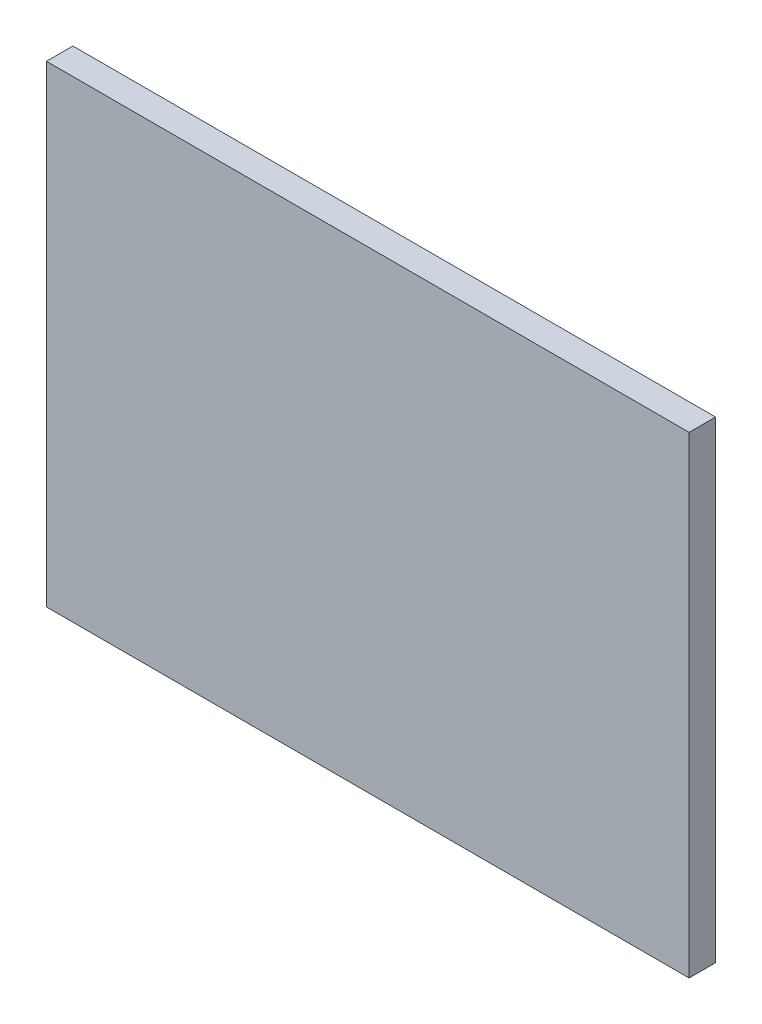
SolidWorks part; units mm, degrees
ref_plane "前视" through (0, 0, 0) normal (0, 0, 1) x (1, 0, 0)
ref_plane "上视" through (0, 0, 0) normal (0, 1, 0) x (1, 0, 0)
ref_plane "右视" through (0, 0, 0) normal (1, 0, 0) x (0, 0, -1)
sketch "草图1" plane through (0, 0, 0) normal (0, 0, 1) x (1, 0, 0)
  line L0 (-97.449, 0) -> (100.3893, 0) construction
  line L1 (-170, 125) -> (170, 125)
  line L2 (-170, 125) -> (-170, -125)
  line L3 (-170, -125) -> (170, -125)
  line L4 (170, 125) -> (170, -125)
  line L5 (-120, 169.1177) -> (-120, -68.0463) construction
  line L7 (-102.0695, 80) -> (112.1504, 80) construction
  line L8 (0, -72.6667) -> (0, 86.108) construction
  circle A0 centre (-120, 80) radius 13
  circle A1 centre (-40, 80) radius 13
  circle A2 centre (-40, 0) radius 13
  circle A3 centre (-120, 0) radius 13
  circle A4 centre (-40, -80) radius 13
  circle A5 centre (-120, -80) radius 13
  circle A6 centre (120, -80) radius 13
  circle A7 centre (40, -80) radius 13
  circle A8 centre (120, 0) radius 13
  circle A9 centre (40, 0) radius 13
  circle A10 centre (40, 80) radius 13
  circle A11 centre (120, 80) radius 13
  dimension "D1" = 250
  dimension "D2" = 340
  dimension "D3" = 80
  dimension "D4" = 50
extrude "基体-拉伸" add sketch "草图1" along normal blind 14
sketch "草图2" plane through (0, 0, 14) normal (0, 0, 1) x (1, 0, 0)
  line L1 (-170, 125) -> (170, 125)
  line L2 (-170, 125) -> (-170, -125)
  line L3 (-170, -125) -> (170, -125)
  line L4 (170, 125) -> (170, -125)
extrude "凸台-拉伸1" add sketch "草图2" against normal blind 14
